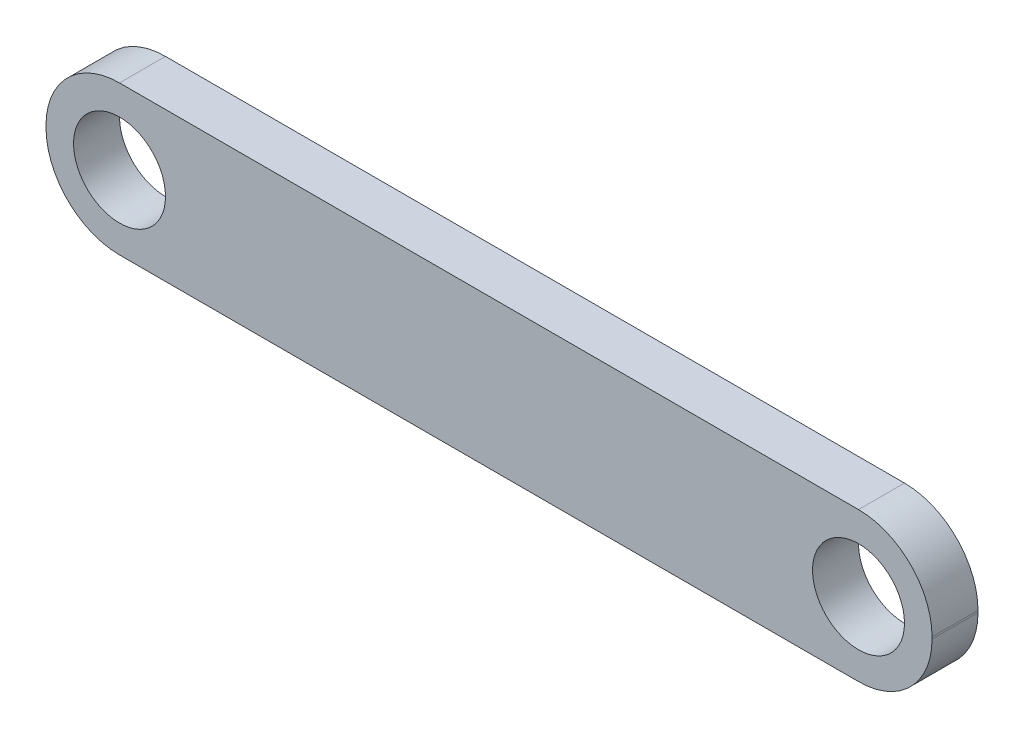
SolidWorks part; units mm, degrees
ref_plane "Front Plane" through (0, 0, 0) normal (0, 0, 1) x (1, 0, 0)
ref_plane "Top Plane" through (0, 0, 0) normal (0, 1, 0) x (1, 0, 0)
ref_plane "Right Plane" through (0, 0, 0) normal (1, 0, 0) x (0, 0, -1)
sketch "Sketch1" plane through (0, 0, 0) normal (0, 0, 1) x (1, 0, 0)
  line L1 (-97.7497, -4.2656) -> (63.056, -4.2656)
  line L2 (-113.7497, -20.2656) -> (-113.7497, -20.6843)
  line L3 (-97.7497, -36.6843) -> (63.056, -36.6843)
  line L4 (79.056, -20.2656) -> (79.056, -20.6843)
  circle A0 centre (-97.7497, -20.6843) radius 10
  arc A1 (-113.7497, -20.6843) -> (-97.7497, -36.6843) centre (-97.7497, -20.6843) ccw
  arc A2 (-97.7497, -4.2656) -> (-113.7497, -20.2656) centre (-97.7497, -20.2656) ccw
  arc A3 (63.056, -36.6843) -> (79.056, -20.6843) centre (63.056, -20.6843) ccw
  arc A4 (63.056, -4.2656) -> (79.056, -20.2656) centre (63.056, -20.2656) cw
  circle A5 centre (63.056, -20.6843) radius 10
  point P8 (0, 0)
  point P15 (-97.7497, -18.9225)
  point P17 (61.7235, -20.6843)
  dimension "D1" = 16
  dimension "D2" = 16
extrude "Boss-Extrude1" add sketch "Sketch1" along normal blind 10
